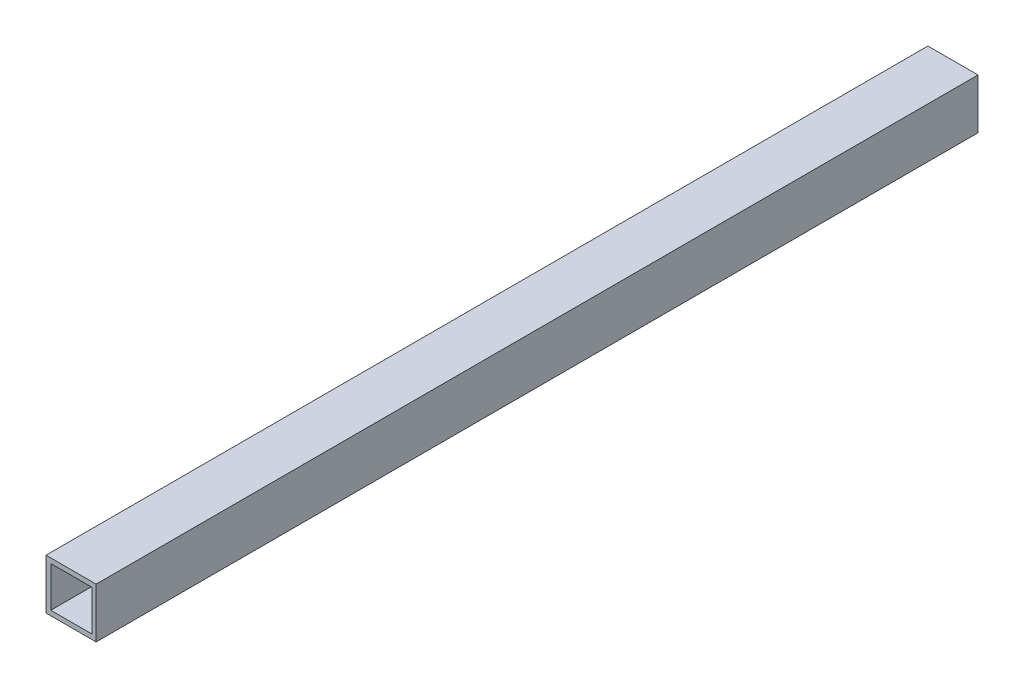
SolidWorks part; units mm, degrees
ref_plane "Front Plane" through (0, 0, 0) normal (0, 0, 1) x (1, 0, 0)
ref_plane "Top Plane" through (0, 0, 0) normal (0, 1, 0) x (1, 0, 0)
ref_plane "Right Plane" through (0, 0, 0) normal (1, 0, 0) x (0, 0, -1)
sketch "Sketch1" plane through (0, 0, 0) normal (0, 0, 1) x (1, 0, 0)
  line L0 (55, 0) -> (-55, 0) construction
  line L2 (0, 0) -> (15.875, 0)
  line L3 (0, 0) -> (0, 15.875)
  line L4 (0, 15.875) -> (15.875, 15.875)
  line L5 (15.875, 0) -> (15.875, 15.875)
  point P0 (0, 0)
  dimension "D1" = 15.875
  dimension "D2" = 15.875
extrude "Boss-Extrude1" add sketch "Sketch1" along normal blind 279.4
sketch "Sketch4" plane through (0, 0, 279.4) normal (0, 0, 1) x (1, 0, 0)
  line L0 (15.875, 15.875) -> (0, 15.875) construction
  line L1 (0, 15.875) -> (0, 0) construction
  line L2 (1.524, 14.351) -> (14.5923, 14.351)
  line L3 (1.524, 14.351) -> (1.524, 1.524)
  line L4 (1.524, 1.524) -> (14.5923, 1.524)
  line L5 (14.5923, 14.351) -> (14.5923, 1.524)
  line L6 (15.875, 0) -> (15.875, 15.875) construction
  line L7 (0, 0) -> (15.875, 0) construction
  point P12 (7.9375, 0)
  dimension "D1" = 1.524
  dimension "D2" = 1.524
  dimension "D3" = 1.2827
  dimension "D4" = 1.524
extrude "Cut-Extrude1" cut sketch "Sketch4" against normal through all
